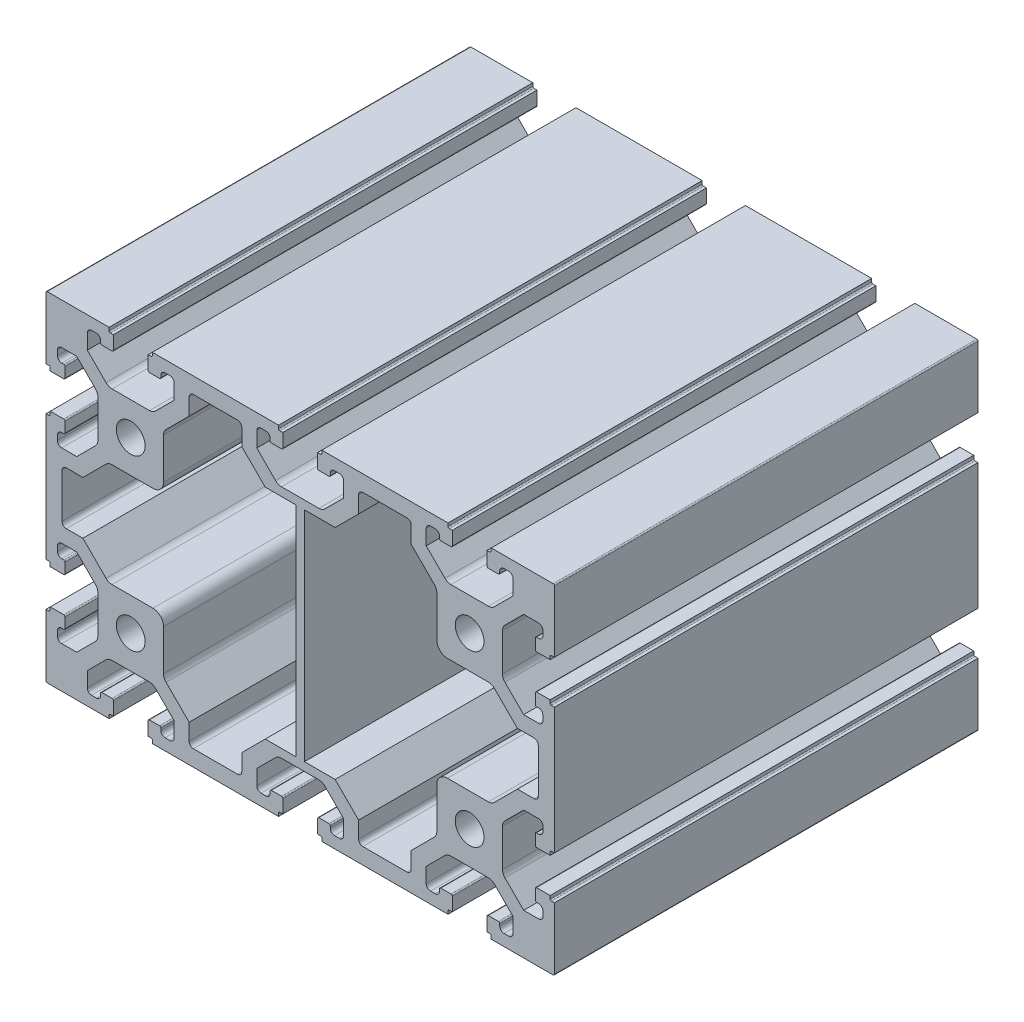
SolidWorks part; units mm, degrees
ref_plane "前视基准面" through (0, 0, 0) normal (0, 0, 1) x (1, 0, 0)
ref_plane "上视基准面" through (0, 0, 0) normal (0, 1, 0) x (1, 0, 0)
ref_plane "右视基准面" through (0, 0, 0) normal (1, 0, 0) x (0, 0, -1)
sketch "草图1" plane through (0, 0, 0) normal (0, 0, 1) x (1, 0, 0)
  line L0 (-45.7894, 39.6553) -> (-60.3894, 39.6553)
  line L1 (-60.6894, 39.3553) -> (-60.6894, 24.7553)
  line L2 (-53.4426, 29.9053) -> (-56.9894, 29.9053)
  line L3 (-57.9894, 28.9053) -> (-57.9894, 27.7553)
  line L4 (-56.9894, 26.7553) -> (-56.4894, 26.7553)
  line L5 (-56.1894, 26.4553) -> (-56.1894, 24.0553)
  line L6 (-56.4894, 23.7553) -> (-59.6894, 23.7553)
  line L8 (-60.6894, 24.7553) -> (-59.9894, 24.7553)
  line L9 (-59.6894, 24.4553) -> (-59.6894, 23.7553)
  line L10 (-53.4426, 29.9053) -> (-49.0252, 25.4879)
  line L11 (-48.4394, 24.0737) -> (-48.4394, 15.2369)
  line L12 (-49.0252, 13.8227) -> (-53.4426, 9.4053)
  line L14 (-51.9763, 5.8653) -> (-46.5221, 11.3195)
  line L15 (-45.1078, 11.9053) -> (-35.4394, 11.9053)
  line L16 (-32.9394, 14.4053) -> (-32.9394, 24.0737)
  line L17 (-32.3536, 25.4879) -> (-26.8994, 30.9421)
  line L18 (-30.4394, 32.4084) -> (-34.8568, 27.9911)
  line L19 (-36.271, 27.4053) -> (-45.1078, 27.4053)
  line L20 (-46.5221, 27.9911) -> (-50.9394, 32.4084)
  line L21 (-45.7894, 39.6553) -> (-45.7894, 38.9553)
  line L22 (-45.4894, 38.6553) -> (-44.7894, 38.6553)
  line L23 (-50.9394, 32.4084) -> (-50.9394, 35.9553)
  line L24 (-49.9394, 36.9553) -> (-48.7894, 36.9553)
  line L25 (-47.7894, 35.9553) -> (-47.7894, 35.4553)
  line L26 (-47.4894, 35.1553) -> (-45.0894, 35.1553)
  line L27 (-44.7894, 35.4553) -> (-44.7894, 38.6553)
  line L28 (-35.5894, 39.6553) -> (-25.1894, 39.6553)
  line L30 (-30.4394, 32.4084) -> (-30.4394, 35.9553)
  line L31 (-31.4394, 36.9553) -> (-32.5894, 36.9553)
  line L32 (-33.5894, 35.9553) -> (-33.5894, 35.4553)
  line L33 (-33.8894, 35.1553) -> (-36.2894, 35.1553)
  line L34 (-36.5894, 35.4553) -> (-36.5894, 38.6553)
  line L35 (-35.5894, 39.6553) -> (-35.5894, 38.9553)
  line L36 (-35.8894, 38.6553) -> (-36.5894, 38.6553)
  line L37 (-53.4426, 9.4053) -> (-56.9894, 9.4053)
  line L38 (-57.9894, 10.4053) -> (-57.9894, 11.5553)
  line L39 (-56.9894, 12.5553) -> (-56.4894, 12.5553)
  line L40 (-56.1894, 12.8553) -> (-56.1894, 15.2553)
  line L41 (-56.4894, 15.5553) -> (-59.6894, 15.5553)
  line L42 (-60.6894, 14.5553) -> (-59.9894, 14.5553)
  line L43 (-59.6894, 14.8553) -> (-59.6894, 15.5553)
  line L44 (-5.7894, 39.6553) -> (-16.1894, 39.6553)
  line L46 (-0.6894, 27.4053) -> (-5.1078, 27.4053)
  line L47 (-6.5221, 27.9911) -> (-10.9394, 32.4084)
  line L48 (-5.7894, 39.6553) -> (-5.7894, 38.9553)
  line L49 (-5.4894, 38.6553) -> (-4.7894, 38.6553)
  line L50 (-10.9394, 32.4084) -> (-10.9394, 35.9553)
  line L51 (-9.9394, 36.9553) -> (-8.7894, 36.9553)
  line L52 (-7.7894, 35.9553) -> (-7.7894, 35.4553)
  line L53 (-7.4894, 35.1553) -> (-5.0894, 35.1553)
  line L54 (-4.7894, 35.4553) -> (-4.7894, 38.6553)
  line L55 (-25.1894, 39.6553) -> (-16.1894, 39.6553)
  line L57 (-26.8994, 30.9421) -> (-26.8994, 34.8553)
  line L58 (-25.8994, 35.8553) -> (-15.4794, 35.8553)
  line L59 (-14.4794, 30.9421) -> (-14.4794, 34.8553)
  line L60 (-45.7894, -40.3447) -> (-60.3894, -40.3447)
  line L61 (-60.6894, -40.0447) -> (-60.6894, -25.4447)
  line L62 (-53.4426, -30.5947) -> (-56.9894, -30.5947)
  line L63 (-57.9894, -29.5947) -> (-57.9894, -28.4447)
  line L64 (-56.9894, -27.4447) -> (-56.4894, -27.4447)
  line L65 (-56.1894, -27.1447) -> (-56.1894, -24.7447)
  line L66 (-56.4894, -24.4447) -> (-59.6894, -24.4447)
  line L68 (-60.6894, -25.4447) -> (-59.9894, -25.4447)
  line L69 (-59.6894, -25.1447) -> (-59.6894, -24.4447)
  line L70 (-53.4426, -30.5947) -> (-49.0252, -26.1773)
  line L71 (-48.4394, -24.7631) -> (-48.4394, -15.9263)
  line L72 (-49.0252, -14.5121) -> (-53.4426, -10.0947)
  line L74 (-51.9763, -6.5547) -> (-46.5221, -12.0089)
  line L75 (-45.1078, -12.5947) -> (-35.4394, -12.5947)
  line L76 (-32.9394, -15.0947) -> (-32.9394, -24.7631)
  line L77 (-32.3536, -26.1773) -> (-26.8994, -31.6316)
  line L78 (-30.4394, -33.0979) -> (-34.8568, -28.6805)
  line L79 (-36.271, -28.0947) -> (-45.1078, -28.0947)
  line L80 (-46.5221, -28.6805) -> (-50.9394, -33.0979)
  line L81 (-45.7894, -40.3447) -> (-45.7894, -39.6447)
  line L82 (-45.4894, -39.3447) -> (-44.7894, -39.3447)
  line L83 (-50.9394, -33.0979) -> (-50.9394, -36.6447)
  line L84 (-49.9394, -37.6447) -> (-48.7894, -37.6447)
  line L85 (-47.7894, -36.6447) -> (-47.7894, -36.1447)
  line L86 (-47.4894, -35.8447) -> (-45.0894, -35.8447)
  line L87 (-44.7894, -36.1447) -> (-44.7894, -39.3447)
  line L88 (-35.5894, -40.3447) -> (-25.1894, -40.3447)
  line L91 (-31.4394, -37.6447) -> (-32.5894, -37.6447)
  line L92 (-33.5894, -36.6447) -> (-33.5894, -36.1447)
  line L93 (-33.8894, -35.8447) -> (-36.2894, -35.8447)
  line L94 (-36.5894, -36.1447) -> (-36.5894, -39.3447)
  line L95 (-35.5894, -40.3447) -> (-35.5894, -39.6447)
  line L96 (-35.8894, -39.3447) -> (-36.5894, -39.3447)
  line L97 (-53.4426, -10.0947) -> (-56.9894, -10.0947)
  line L98 (-57.9894, -11.0947) -> (-57.9894, -12.2447)
  line L99 (-56.9894, -13.2447) -> (-56.4894, -13.2447)
  line L100 (-56.1894, -13.5447) -> (-56.1894, -15.9447)
  line L101 (-56.4894, -16.2447) -> (-59.6894, -16.2447)
  line L102 (-60.6894, -15.2447) -> (-59.9894, -15.2447)
  line L103 (-59.6894, -15.5447) -> (-59.6894, -16.2447)
  line L104 (-5.7894, -40.3447) -> (-16.1894, -40.3447)
  line L106 (-14.4794, -31.6316) -> (-8.9426, -26.0947)
  line L107 (-0.6894, -28.0947) -> (-5.1078, -28.0947)
  line L108 (-6.5221, -28.6805) -> (-10.9394, -33.0979)
  line L109 (-1.6894, -26.0947) -> (-8.9426, -26.0947)
  line L110 (-5.7894, -40.3447) -> (-5.7894, -39.6447)
  line L111 (-5.4894, -39.3447) -> (-4.7894, -39.3447)
  line L112 (-10.9394, -33.0979) -> (-10.9394, -36.6447)
  line L113 (-9.9394, -37.6447) -> (-8.7894, -37.6447)
  line L114 (-7.7894, -36.6447) -> (-7.7894, -36.1447)
  line L115 (-7.4894, -35.8447) -> (-5.0894, -35.8447)
  line L116 (-4.7894, -36.1447) -> (-4.7894, -39.3447)
  line L117 (-25.1894, -40.3447) -> (-16.1894, -40.3447)
  line L118 (-30.4394, -33.0979) -> (-30.4394, -36.6447)
  line L119 (-26.8994, -31.6316) -> (-26.8994, -35.5447)
  line L120 (-25.8994, -36.5447) -> (-15.4794, -36.5447)
  line L121 (-14.4794, -31.6316) -> (-14.4794, -35.5447)
  line L122 (-51.9763, 5.8653) -> (-55.8894, 5.8653)
  line L123 (-56.8894, 4.8653) -> (-56.8894, -5.5547)
  line L124 (-51.9763, -6.5547) -> (-55.8894, -6.5547)
  line L125 (-60.6894, 14.5553) -> (-60.6894, 4.1553)
  line L126 (-60.6894, -15.2447) -> (-60.6894, -4.8447)
  line L127 (-60.6894, 4.1553) -> (-60.6894, -4.8447)
  line L128 (-14.4794, 30.9421) -> (-8.9426, 25.4053)
  line L129 (-1.6894, 25.4053) -> (-1.6894, -26.0947)
  line L130 (-1.6894, 25.4053) -> (-8.9426, 25.4053)
  line L131 (44.4106, 39.6553) -> (59.0106, 39.6553)
  line L132 (59.3106, 39.3553) -> (59.3106, 24.7553)
  line L133 (52.0637, 29.9053) -> (55.6106, 29.9053)
  line L134 (56.6106, 28.9053) -> (56.6106, 27.7553)
  line L135 (55.6106, 26.7553) -> (55.1106, 26.7553)
  line L136 (54.8106, 26.4553) -> (54.8106, 24.0553)
  line L137 (55.1106, 23.7553) -> (58.3106, 23.7553)
  line L139 (59.3106, 24.7553) -> (58.6106, 24.7553)
  line L140 (58.3106, 24.4553) -> (58.3106, 23.7553)
  line L141 (52.0637, 29.9053) -> (47.6464, 25.4879)
  line L142 (47.0606, 24.0737) -> (47.0606, 15.2369)
  line L143 (47.6464, 13.8227) -> (52.0637, 9.4053)
  line L145 (50.5974, 5.8653) -> (45.1432, 11.3195)
  line L146 (43.729, 11.9053) -> (34.0606, 11.9053)
  line L147 (31.5606, 14.4053) -> (31.5606, 24.0737)
  line L148 (30.9748, 25.4879) -> (25.5206, 30.9421)
  line L149 (29.0606, 32.4084) -> (33.4779, 27.9911)
  line L150 (34.8922, 27.4053) -> (43.729, 27.4053)
  line L151 (45.1432, 27.9911) -> (49.5606, 32.4084)
  line L152 (44.4106, 39.6553) -> (44.4106, 38.9553)
  line L153 (44.1106, 38.6553) -> (43.4106, 38.6553)
  line L154 (49.5606, 32.4084) -> (49.5606, 35.9553)
  line L155 (48.5606, 36.9553) -> (47.4106, 36.9553)
  line L156 (46.4106, 35.9553) -> (46.4106, 35.4553)
  line L157 (46.1106, 35.1553) -> (43.7106, 35.1553)
  line L158 (43.4106, 35.4553) -> (43.4106, 38.6553)
  line L159 (34.2106, 39.6553) -> (23.8106, 39.6553)
  line L161 (29.0606, 32.4084) -> (29.0606, 35.9553)
  line L162 (30.0606, 36.9553) -> (31.2106, 36.9553)
  line L163 (32.2106, 35.9553) -> (32.2106, 35.4553)
  line L164 (32.5106, 35.1553) -> (34.9106, 35.1553)
  line L165 (35.2106, 35.4553) -> (35.2106, 38.6553)
  line L166 (34.2106, 39.6553) -> (34.2106, 38.9553)
  line L167 (34.5106, 38.6553) -> (35.2106, 38.6553)
  line L168 (52.0637, 9.4053) -> (55.6106, 9.4053)
  line L169 (56.6106, 10.4053) -> (56.6106, 11.5553)
  line L170 (55.6106, 12.5553) -> (55.1106, 12.5553)
  line L171 (54.8106, 12.8553) -> (54.8106, 15.2553)
  line L172 (55.1106, 15.5553) -> (58.3106, 15.5553)
  line L173 (59.3106, 14.5553) -> (58.6106, 14.5553)
  line L174 (58.3106, 14.8553) -> (58.3106, 15.5553)
  line L175 (4.4106, 39.6553) -> (14.8106, 39.6553)
  line L177 (-0.6894, 27.4053) -> (3.729, 27.4053)
  line L178 (5.1432, 27.9911) -> (9.5606, 32.4084)
  line L179 (4.4106, 39.6553) -> (4.4106, 38.9553)
  line L180 (4.1106, 38.6553) -> (3.4106, 38.6553)
  line L181 (9.5606, 32.4084) -> (9.5606, 35.9553)
  line L182 (8.5606, 36.9553) -> (7.4106, 36.9553)
  line L183 (6.4106, 35.9553) -> (6.4106, 35.4553)
  line L184 (6.1106, 35.1553) -> (3.7106, 35.1553)
  line L185 (3.4106, 35.4553) -> (3.4106, 38.6553)
  line L186 (23.8106, 39.6553) -> (14.8106, 39.6553)
  line L188 (25.5206, 30.9421) -> (25.5206, 34.8553)
  line L189 (24.5206, 35.8553) -> (14.1006, 35.8553)
  line L190 (13.1006, 30.9421) -> (13.1006, 34.8553)
  line L191 (44.4106, -40.3447) -> (59.0106, -40.3447)
  line L192 (59.3106, -40.0447) -> (59.3106, -25.4447)
  line L193 (52.0637, -30.5947) -> (55.6106, -30.5947)
  line L194 (56.6106, -29.5947) -> (56.6106, -28.4447)
  line L195 (55.6106, -27.4447) -> (55.1106, -27.4447)
  line L196 (54.8106, -27.1447) -> (54.8106, -24.7447)
  line L197 (55.1106, -24.4447) -> (58.3106, -24.4447)
  line L199 (59.3106, -25.4447) -> (58.6106, -25.4447)
  line L200 (58.3106, -25.1447) -> (58.3106, -24.4447)
  line L201 (52.0637, -30.5947) -> (47.6464, -26.1773)
  line L202 (47.0606, -24.7631) -> (47.0606, -15.9263)
  line L203 (47.6464, -14.5121) -> (52.0637, -10.0947)
  line L205 (50.5974, -6.5547) -> (45.1432, -12.0089)
  line L206 (43.729, -12.5947) -> (34.0606, -12.5947)
  line L207 (31.5606, -15.0947) -> (31.5606, -24.7631)
  line L208 (30.9748, -26.1773) -> (25.5206, -31.6316)
  line L209 (29.0606, -33.0979) -> (33.4779, -28.6805)
  line L210 (34.8922, -28.0947) -> (43.729, -28.0947)
  line L211 (45.1432, -28.6805) -> (49.5606, -33.0979)
  line L212 (44.4106, -40.3447) -> (44.4106, -39.6447)
  line L213 (44.1106, -39.3447) -> (43.4106, -39.3447)
  line L214 (49.5606, -33.0979) -> (49.5606, -36.6447)
  line L215 (48.5606, -37.6447) -> (47.4106, -37.6447)
  line L216 (46.4106, -36.6447) -> (46.4106, -36.1447)
  line L217 (46.1106, -35.8447) -> (43.7106, -35.8447)
  line L218 (43.4106, -36.1447) -> (43.4106, -39.3447)
  line L219 (34.2106, -40.3447) -> (23.8106, -40.3447)
  line L222 (30.0606, -37.6447) -> (31.2106, -37.6447)
  line L223 (32.2106, -36.6447) -> (32.2106, -36.1447)
  line L224 (32.5106, -35.8447) -> (34.9106, -35.8447)
  line L225 (35.2106, -36.1447) -> (35.2106, -39.3447)
  line L226 (34.2106, -40.3447) -> (34.2106, -39.6447)
  line L227 (34.5106, -39.3447) -> (35.2106, -39.3447)
  line L228 (52.0637, -10.0947) -> (55.6106, -10.0947)
  line L229 (56.6106, -11.0947) -> (56.6106, -12.2447)
  line L230 (55.6106, -13.2447) -> (55.1106, -13.2447)
  line L231 (54.8106, -13.5447) -> (54.8106, -15.9447)
  line L232 (55.1106, -16.2447) -> (58.3106, -16.2447)
  line L233 (59.3106, -15.2447) -> (58.6106, -15.2447)
  line L234 (58.3106, -15.5447) -> (58.3106, -16.2447)
  line L235 (4.4106, -40.3447) -> (14.8106, -40.3447)
  line L237 (13.1006, -31.6316) -> (7.5637, -26.0947)
  line L238 (-0.6894, -28.0947) -> (3.729, -28.0947)
  line L239 (5.1432, -28.6805) -> (9.5606, -33.0979)
  line L240 (0.3106, -26.0947) -> (7.5637, -26.0947)
  line L241 (4.4106, -40.3447) -> (4.4106, -39.6447)
  line L242 (4.1106, -39.3447) -> (3.4106, -39.3447)
  line L243 (9.5606, -33.0979) -> (9.5606, -36.6447)
  line L244 (8.5606, -37.6447) -> (7.4106, -37.6447)
  line L245 (6.4106, -36.6447) -> (6.4106, -36.1447)
  line L246 (6.1106, -35.8447) -> (3.7106, -35.8447)
  line L247 (3.4106, -36.1447) -> (3.4106, -39.3447)
  line L248 (23.8106, -40.3447) -> (14.8106, -40.3447)
  line L249 (29.0606, -33.0979) -> (29.0606, -36.6447)
  line L250 (25.5206, -31.6316) -> (25.5206, -35.5447)
  line L251 (24.5206, -36.5447) -> (14.1006, -36.5447)
  line L252 (13.1006, -31.6316) -> (13.1006, -35.5447)
  line L253 (50.5974, 5.8653) -> (54.5106, 5.8653)
  line L254 (55.5106, 4.8653) -> (55.5106, -5.5547)
  line L255 (50.5974, -6.5547) -> (54.5106, -6.5547)
  line L256 (59.3106, 14.5553) -> (59.3106, 4.1553)
  line L257 (59.3106, -15.2447) -> (59.3106, -4.8447)
  line L258 (59.3106, 4.1553) -> (59.3106, -4.8447)
  line L259 (13.1006, 30.9421) -> (7.5637, 25.4053)
  line L260 (0.3106, 25.4053) -> (7.5637, 25.4053)
  line L261 (0.3106, 25.4053) -> (0.3106, -26.0947)
  arc A0 (-60.3894, 39.6553) -> (-60.6894, 39.3553) centre (-60.3894, 39.3553) ccw
  arc A1 (-56.9894, 29.9053) -> (-57.9894, 28.9053) centre (-56.9894, 28.9053) ccw
  arc A2 (-57.9894, 27.7553) -> (-56.9894, 26.7553) centre (-56.9894, 27.7553) ccw
  arc A3 (-56.1894, 26.4553) -> (-56.4894, 26.7553) centre (-56.4894, 26.4553) ccw
  arc A4 (-56.4894, 23.7553) -> (-56.1894, 24.0553) centre (-56.4894, 24.0553) ccw
  arc A5 (-59.6894, 24.4553) -> (-59.9894, 24.7553) centre (-59.9894, 24.4553) ccw
  arc A6 (-48.4394, 24.0737) -> (-49.0252, 25.4879) centre (-50.4394, 24.0737) ccw
  arc A7 (-49.0252, 13.8227) -> (-48.4394, 15.2369) centre (-50.4394, 15.2369) ccw
  arc A8 (-45.1078, 11.9053) -> (-46.5221, 11.3195) centre (-45.1078, 9.9053) ccw
  arc A9 (-35.4394, 11.9053) -> (-32.9394, 14.4053) centre (-35.4394, 14.4053) ccw
  arc A10 (-32.3536, 25.4879) -> (-32.9394, 24.0737) centre (-30.9394, 24.0737) ccw
  arc A11 (-36.271, 27.4053) -> (-34.8568, 27.9911) centre (-36.271, 29.4053) ccw
  arc A12 (-46.5221, 27.9911) -> (-45.1078, 27.4053) centre (-45.1078, 29.4053) ccw
  circle A13 centre (-40.6894, 19.6553) radius 3.4
  arc A14 (-45.7894, 38.9553) -> (-45.4894, 38.6553) centre (-45.4894, 38.9553) ccw
  arc A15 (-49.9394, 36.9553) -> (-50.9394, 35.9553) centre (-49.9394, 35.9553) ccw
  arc A16 (-47.7894, 35.9553) -> (-48.7894, 36.9553) centre (-48.7894, 35.9553) ccw
  arc A17 (-47.7894, 35.4553) -> (-47.4894, 35.1553) centre (-47.4894, 35.4553) ccw
  arc A18 (-45.0894, 35.1553) -> (-44.7894, 35.4553) centre (-45.0894, 35.4553) ccw
  arc A19 (-30.4394, 35.9553) -> (-31.4394, 36.9553) centre (-31.4394, 35.9553) ccw
  arc A20 (-32.5894, 36.9553) -> (-33.5894, 35.9553) centre (-32.5894, 35.9553) ccw
  arc A21 (-33.8894, 35.1553) -> (-33.5894, 35.4553) centre (-33.8894, 35.4553) ccw
  arc A22 (-36.5894, 35.4553) -> (-36.2894, 35.1553) centre (-36.2894, 35.4553) ccw
  arc A23 (-35.8894, 38.6553) -> (-35.5894, 38.9553) centre (-35.8894, 38.9553) ccw
  arc A24 (-57.9894, 10.4053) -> (-56.9894, 9.4053) centre (-56.9894, 10.4053) ccw
  arc A25 (-56.9894, 12.5553) -> (-57.9894, 11.5553) centre (-56.9894, 11.5553) ccw
  arc A26 (-56.4894, 12.5553) -> (-56.1894, 12.8553) centre (-56.4894, 12.8553) ccw
  arc A27 (-56.1894, 15.2553) -> (-56.4894, 15.5553) centre (-56.4894, 15.2553) ccw
  arc A28 (-59.9894, 14.5553) -> (-59.6894, 14.8553) centre (-59.9894, 14.8553) ccw
  arc A29 (-6.5221, 27.9911) -> (-5.1078, 27.4053) centre (-5.1078, 29.4053) ccw
  arc A30 (-5.7894, 38.9553) -> (-5.4894, 38.6553) centre (-5.4894, 38.9553) ccw
  arc A31 (-9.9394, 36.9553) -> (-10.9394, 35.9553) centre (-9.9394, 35.9553) ccw
  arc A32 (-7.7894, 35.9553) -> (-8.7894, 36.9553) centre (-8.7894, 35.9553) ccw
  arc A33 (-7.7894, 35.4553) -> (-7.4894, 35.1553) centre (-7.4894, 35.4553) ccw
  arc A34 (-5.0894, 35.1553) -> (-4.7894, 35.4553) centre (-5.0894, 35.4553) ccw
  arc A35 (-25.8994, 35.8553) -> (-26.8994, 34.8553) centre (-25.8994, 34.8553) ccw
  arc A36 (-14.4794, 34.8553) -> (-15.4794, 35.8553) centre (-15.4794, 34.8553) ccw
  arc A37 (-60.6894, -40.0447) -> (-60.3894, -40.3447) centre (-60.3894, -40.0447) ccw
  arc A38 (-57.9894, -29.5947) -> (-56.9894, -30.5947) centre (-56.9894, -29.5947) ccw
  arc A39 (-56.9894, -27.4447) -> (-57.9894, -28.4447) centre (-56.9894, -28.4447) ccw
  arc A40 (-56.4894, -27.4447) -> (-56.1894, -27.1447) centre (-56.4894, -27.1447) ccw
  arc A41 (-56.1894, -24.7447) -> (-56.4894, -24.4447) centre (-56.4894, -24.7447) ccw
  arc A42 (-59.9894, -25.4447) -> (-59.6894, -25.1447) centre (-59.9894, -25.1447) ccw
  arc A43 (-49.0252, -26.1773) -> (-48.4394, -24.7631) centre (-50.4394, -24.7631) ccw
  arc A44 (-48.4394, -15.9263) -> (-49.0252, -14.5121) centre (-50.4394, -15.9263) ccw
  arc A45 (-46.5221, -12.0089) -> (-45.1078, -12.5947) centre (-45.1078, -10.5947) ccw
  arc A46 (-32.9394, -15.0947) -> (-35.4394, -12.5947) centre (-35.4394, -15.0947) ccw
  arc A47 (-32.9394, -24.7631) -> (-32.3536, -26.1773) centre (-30.9394, -24.7631) ccw
  arc A48 (-34.8568, -28.6805) -> (-36.271, -28.0947) centre (-36.271, -30.0947) ccw
  arc A49 (-45.1078, -28.0947) -> (-46.5221, -28.6805) centre (-45.1078, -30.0947) ccw
  circle A50 centre (-40.6894, -20.3447) radius 3.4
  arc A51 (-45.4894, -39.3447) -> (-45.7894, -39.6447) centre (-45.4894, -39.6447) ccw
  arc A52 (-50.9394, -36.6447) -> (-49.9394, -37.6447) centre (-49.9394, -36.6447) ccw
  arc A53 (-48.7894, -37.6447) -> (-47.7894, -36.6447) centre (-48.7894, -36.6447) ccw
  arc A54 (-47.4894, -35.8447) -> (-47.7894, -36.1447) centre (-47.4894, -36.1447) ccw
  arc A55 (-44.7894, -36.1447) -> (-45.0894, -35.8447) centre (-45.0894, -36.1447) ccw
  arc A56 (-31.4394, -37.6447) -> (-30.4394, -36.6447) centre (-31.4394, -36.6447) ccw
  arc A57 (-33.5894, -36.6447) -> (-32.5894, -37.6447) centre (-32.5894, -36.6447) ccw
  arc A58 (-33.5894, -36.1447) -> (-33.8894, -35.8447) centre (-33.8894, -36.1447) ccw
  arc A59 (-36.2894, -35.8447) -> (-36.5894, -36.1447) centre (-36.2894, -36.1447) ccw
  arc A60 (-35.5894, -39.6447) -> (-35.8894, -39.3447) centre (-35.8894, -39.6447) ccw
  arc A61 (-56.9894, -10.0947) -> (-57.9894, -11.0947) centre (-56.9894, -11.0947) ccw
  arc A62 (-57.9894, -12.2447) -> (-56.9894, -13.2447) centre (-56.9894, -12.2447) ccw
  arc A63 (-56.1894, -13.5447) -> (-56.4894, -13.2447) centre (-56.4894, -13.5447) ccw
  arc A64 (-56.4894, -16.2447) -> (-56.1894, -15.9447) centre (-56.4894, -15.9447) ccw
  arc A65 (-59.6894, -15.5447) -> (-59.9894, -15.2447) centre (-59.9894, -15.5447) ccw
  arc A66 (-5.1078, -28.0947) -> (-6.5221, -28.6805) centre (-5.1078, -30.0947) ccw
  arc A67 (-5.4894, -39.3447) -> (-5.7894, -39.6447) centre (-5.4894, -39.6447) ccw
  arc A68 (-10.9394, -36.6447) -> (-9.9394, -37.6447) centre (-9.9394, -36.6447) ccw
  arc A69 (-8.7894, -37.6447) -> (-7.7894, -36.6447) centre (-8.7894, -36.6447) ccw
  arc A70 (-7.4894, -35.8447) -> (-7.7894, -36.1447) centre (-7.4894, -36.1447) ccw
  arc A71 (-4.7894, -36.1447) -> (-5.0894, -35.8447) centre (-5.0894, -36.1447) ccw
  arc A72 (-26.8994, -35.5447) -> (-25.8994, -36.5447) centre (-25.8994, -35.5447) ccw
  arc A73 (-15.4794, -36.5447) -> (-14.4794, -35.5447) centre (-15.4794, -35.5447) ccw
  arc A74 (-55.8894, 5.8653) -> (-56.8894, 4.8653) centre (-55.8894, 4.8653) ccw
  arc A75 (-56.8894, -5.5547) -> (-55.8894, -6.5547) centre (-55.8894, -5.5547) ccw
  arc A76 (59.3106, 39.3553) -> (59.0106, 39.6553) centre (59.0106, 39.3553) ccw
  arc A77 (56.6106, 28.9053) -> (55.6106, 29.9053) centre (55.6106, 28.9053) ccw
  arc A78 (55.6106, 26.7553) -> (56.6106, 27.7553) centre (55.6106, 27.7553) ccw
  arc A79 (55.1106, 26.7553) -> (54.8106, 26.4553) centre (55.1106, 26.4553) ccw
  arc A80 (54.8106, 24.0553) -> (55.1106, 23.7553) centre (55.1106, 24.0553) ccw
  arc A81 (58.6106, 24.7553) -> (58.3106, 24.4553) centre (58.6106, 24.4553) ccw
  arc A82 (47.6464, 25.4879) -> (47.0606, 24.0737) centre (49.0606, 24.0737) ccw
  arc A83 (47.0606, 15.2369) -> (47.6464, 13.8227) centre (49.0606, 15.2369) ccw
  arc A84 (45.1432, 11.3195) -> (43.729, 11.9053) centre (43.729, 9.9053) ccw
  arc A85 (31.5606, 14.4053) -> (34.0606, 11.9053) centre (34.0606, 14.4053) ccw
  arc A86 (31.5606, 24.0737) -> (30.9748, 25.4879) centre (29.5606, 24.0737) ccw
  arc A87 (33.4779, 27.9911) -> (34.8922, 27.4053) centre (34.8922, 29.4053) ccw
  arc A88 (43.729, 27.4053) -> (45.1432, 27.9911) centre (43.729, 29.4053) ccw
  circle A89 centre (39.3106, 19.6553) radius 3.4
  arc A90 (44.1106, 38.6553) -> (44.4106, 38.9553) centre (44.1106, 38.9553) ccw
  arc A91 (49.5606, 35.9553) -> (48.5606, 36.9553) centre (48.5606, 35.9553) ccw
  arc A92 (47.4106, 36.9553) -> (46.4106, 35.9553) centre (47.4106, 35.9553) ccw
  arc A93 (46.1106, 35.1553) -> (46.4106, 35.4553) centre (46.1106, 35.4553) ccw
  arc A94 (43.4106, 35.4553) -> (43.7106, 35.1553) centre (43.7106, 35.4553) ccw
  arc A95 (30.0606, 36.9553) -> (29.0606, 35.9553) centre (30.0606, 35.9553) ccw
  arc A96 (32.2106, 35.9553) -> (31.2106, 36.9553) centre (31.2106, 35.9553) ccw
  arc A97 (32.2106, 35.4553) -> (32.5106, 35.1553) centre (32.5106, 35.4553) ccw
  arc A98 (34.9106, 35.1553) -> (35.2106, 35.4553) centre (34.9106, 35.4553) ccw
  arc A99 (34.2106, 38.9553) -> (34.5106, 38.6553) centre (34.5106, 38.9553) ccw
  arc A100 (55.6106, 9.4053) -> (56.6106, 10.4053) centre (55.6106, 10.4053) ccw
  arc A101 (56.6106, 11.5553) -> (55.6106, 12.5553) centre (55.6106, 11.5553) ccw
  arc A102 (54.8106, 12.8553) -> (55.1106, 12.5553) centre (55.1106, 12.8553) ccw
  arc A103 (55.1106, 15.5553) -> (54.8106, 15.2553) centre (55.1106, 15.2553) ccw
  arc A104 (58.3106, 14.8553) -> (58.6106, 14.5553) centre (58.6106, 14.8553) ccw
  arc A105 (3.729, 27.4053) -> (5.1432, 27.9911) centre (3.729, 29.4053) ccw
  arc A106 (4.1106, 38.6553) -> (4.4106, 38.9553) centre (4.1106, 38.9553) ccw
  arc A107 (9.5606, 35.9553) -> (8.5606, 36.9553) centre (8.5606, 35.9553) ccw
  arc A108 (7.4106, 36.9553) -> (6.4106, 35.9553) centre (7.4106, 35.9553) ccw
  arc A109 (6.1106, 35.1553) -> (6.4106, 35.4553) centre (6.1106, 35.4553) ccw
  arc A110 (3.4106, 35.4553) -> (3.7106, 35.1553) centre (3.7106, 35.4553) ccw
  arc A111 (25.5206, 34.8553) -> (24.5206, 35.8553) centre (24.5206, 34.8553) ccw
  arc A112 (14.1006, 35.8553) -> (13.1006, 34.8553) centre (14.1006, 34.8553) ccw
  arc A113 (59.0106, -40.3447) -> (59.3106, -40.0447) centre (59.0106, -40.0447) ccw
  arc A114 (55.6106, -30.5947) -> (56.6106, -29.5947) centre (55.6106, -29.5947) ccw
  arc A115 (56.6106, -28.4447) -> (55.6106, -27.4447) centre (55.6106, -28.4447) ccw
  arc A116 (54.8106, -27.1447) -> (55.1106, -27.4447) centre (55.1106, -27.1447) ccw
  arc A117 (55.1106, -24.4447) -> (54.8106, -24.7447) centre (55.1106, -24.7447) ccw
  arc A118 (58.3106, -25.1447) -> (58.6106, -25.4447) centre (58.6106, -25.1447) ccw
  arc A119 (47.0606, -24.7631) -> (47.6464, -26.1773) centre (49.0606, -24.7631) ccw
  arc A120 (47.6464, -14.5121) -> (47.0606, -15.9263) centre (49.0606, -15.9263) ccw
  arc A121 (43.729, -12.5947) -> (45.1432, -12.0089) centre (43.729, -10.5947) ccw
  arc A122 (34.0606, -12.5947) -> (31.5606, -15.0947) centre (34.0606, -15.0947) ccw
  arc A123 (30.9748, -26.1773) -> (31.5606, -24.7631) centre (29.5606, -24.7631) ccw
  arc A124 (34.8922, -28.0947) -> (33.4779, -28.6805) centre (34.8922, -30.0947) ccw
  arc A125 (45.1432, -28.6805) -> (43.729, -28.0947) centre (43.729, -30.0947) ccw
  circle A126 centre (39.3106, -20.3447) radius 3.4
  arc A127 (44.4106, -39.6447) -> (44.1106, -39.3447) centre (44.1106, -39.6447) ccw
  arc A128 (48.5606, -37.6447) -> (49.5606, -36.6447) centre (48.5606, -36.6447) ccw
  arc A129 (46.4106, -36.6447) -> (47.4106, -37.6447) centre (47.4106, -36.6447) ccw
  arc A130 (46.4106, -36.1447) -> (46.1106, -35.8447) centre (46.1106, -36.1447) ccw
  arc A131 (43.7106, -35.8447) -> (43.4106, -36.1447) centre (43.7106, -36.1447) ccw
  arc A132 (29.0606, -36.6447) -> (30.0606, -37.6447) centre (30.0606, -36.6447) ccw
  arc A133 (31.2106, -37.6447) -> (32.2106, -36.6447) centre (31.2106, -36.6447) ccw
  arc A134 (32.5106, -35.8447) -> (32.2106, -36.1447) centre (32.5106, -36.1447) ccw
  arc A135 (35.2106, -36.1447) -> (34.9106, -35.8447) centre (34.9106, -36.1447) ccw
  arc A136 (34.5106, -39.3447) -> (34.2106, -39.6447) centre (34.5106, -39.6447) ccw
  arc A137 (56.6106, -11.0947) -> (55.6106, -10.0947) centre (55.6106, -11.0947) ccw
  arc A138 (55.6106, -13.2447) -> (56.6106, -12.2447) centre (55.6106, -12.2447) ccw
  arc A139 (55.1106, -13.2447) -> (54.8106, -13.5447) centre (55.1106, -13.5447) ccw
  arc A140 (54.8106, -15.9447) -> (55.1106, -16.2447) centre (55.1106, -15.9447) ccw
  arc A141 (58.6106, -15.2447) -> (58.3106, -15.5447) centre (58.6106, -15.5447) ccw
  arc A142 (5.1432, -28.6805) -> (3.729, -28.0947) centre (3.729, -30.0947) ccw
  arc A143 (4.4106, -39.6447) -> (4.1106, -39.3447) centre (4.1106, -39.6447) ccw
  arc A144 (8.5606, -37.6447) -> (9.5606, -36.6447) centre (8.5606, -36.6447) ccw
  arc A145 (6.4106, -36.6447) -> (7.4106, -37.6447) centre (7.4106, -36.6447) ccw
  arc A146 (6.4106, -36.1447) -> (6.1106, -35.8447) centre (6.1106, -36.1447) ccw
  arc A147 (3.7106, -35.8447) -> (3.4106, -36.1447) centre (3.7106, -36.1447) ccw
  arc A148 (24.5206, -36.5447) -> (25.5206, -35.5447) centre (24.5206, -35.5447) ccw
  arc A149 (13.1006, -35.5447) -> (14.1006, -36.5447) centre (14.1006, -35.5447) ccw
  arc A150 (55.5106, 4.8653) -> (54.5106, 5.8653) centre (54.5106, 4.8653) ccw
  arc A151 (54.5106, -6.5547) -> (55.5106, -5.5547) centre (54.5106, -5.5547) ccw
extrude "凸台-拉伸1" add sketch "草图1" along normal blind 100
